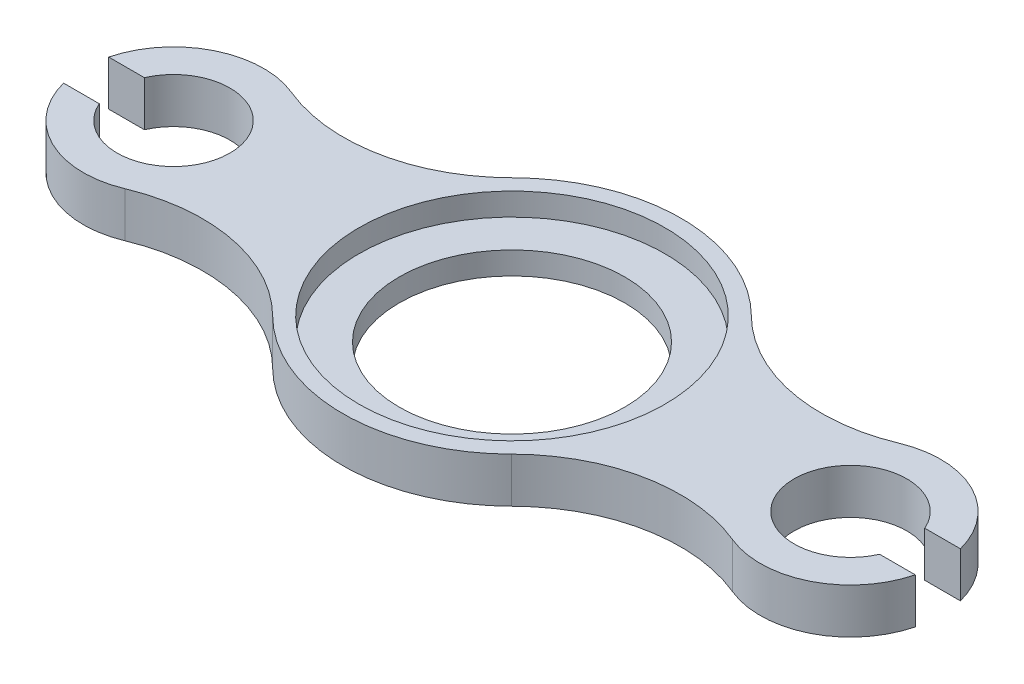
SolidWorks part; units mm, degrees
material "AISI 1020"
ref_plane "Plan de face" through (0, 0, 0) normal (0, 0, 1) x (1, 0, 0)
ref_plane "Plan de dessus" through (0, 0, 0) normal (0, 1, 0) x (1, 0, 0)
ref_plane "Plan de droite" through (0, 0, 0) normal (1, 0, 0) x (0, 0, -1)
sketch "Esquisse1" plane through (0, 0, 0) normal (0, 1, 0) x (1, 0, 0)
  line L0 (-362.0178, 0) -> (302.6706, 0) construction
  line L1 (0, 245.9199) -> (0, -219.9555) construction
  line L2 (-150, 208.8279) -> (-150, -184.3472) construction
  line L3 (150, 245.9199) -> (150, -239.2433) construction
  arc A0 (-52.9583, -53.1076) -> (52.9583, -53.1076) centre (0, 0) ccw
  arc A1 (-134.6667, 36.9444) -> (-134.6667, -36.9444) centre (-150, 0) ccw
  arc A3 (-134.6667, 36.9444) -> (-52.9583, 53.1076) centre (-105.9167, 106.2152) ccw
  arc A4 (-134.6667, -36.9444) -> (-52.9583, -53.1076) centre (-105.9167, -106.2152) cw
  arc A6 (134.6667, 36.9444) -> (134.6667, -36.9444) centre (150, 0) cw
  arc A7 (134.6667, -36.9444) -> (52.9583, -53.1076) centre (105.9167, -106.2152) ccw
  arc A8 (134.6667, 36.9444) -> (52.9583, 53.1076) centre (105.9167, 106.2152) cw
  arc A9 (52.9583, 53.1076) -> (-52.9583, 53.1076) centre (0, 0) ccw
  dimension "D3" = 150
  dimension "D4" = 80
  dimension "D6" = 150
  dimension "D1" = 150
  dimension "D2" = 150
extrude "Boss.-Extru.1" add sketch "Esquisse1" along normal blind 20
sketch "Esquisse2" plane through (0, 20, 0) normal (0, 1, 0) x (1, 0, 0)
  circle A0 centre (0, 0) radius 50
  dimension "D1" = 100
extrude "Enlèv. mat.-Extru.1" cut sketch "Esquisse2" against normal through all
sketch "Esquisse3" plane through (0, 20, 0) normal (0, 1, 0) x (1, 0, 0)
  circle A0 centre (0, 0) radius 67.8
  dimension "D1" = 135.6
extrude "Enlèv. mat.-Extru.2" cut sketch "Esquisse3" against normal blind 10
sketch "Esquisse4" plane through (0, 20, 0) normal (0, 1, 0) x (1, 0, 0)
  line L0 (0, 136.3023) -> (0, -137.5359) construction
  line L1 (-259.0361, 0) -> (262.3255, 0) construction
  circle A0 centre (-150, 0) radius 25
  circle A1 centre (150, 0) radius 25
  dimension "D1" = 50
extrude "Enlèv. mat.-Extru.4" cut sketch "Esquisse4" against normal through all
sketch "Esquisse5" plane through (0, 20, 0) normal (0, 1, 0) x (1, 0, 0)
  line L0 (-210.1071, 0) -> (235.1884, 0) construction
  line L1 (0, 119.8556) -> (0, -115.3328) construction
  line L2 (-188.7298, -10) -> (-172.9129, -10)
  line L3 (-188.7298, 10) -> (-172.9129, 10)
  line L4 (188.7298, -10) -> (172.9129, -10)
  line L5 (188.7298, 10) -> (172.9129, 10)
  arc A0 (-188.7298, 10) -> (-188.7298, -10) centre (-150, 0) ccw
  arc A1 (-172.9129, 10) -> (-172.9129, -10) centre (-150, 0) ccw
  arc A2 (188.7298, 10) -> (188.7298, -10) centre (150, 0) cw
  arc A3 (172.9129, 10) -> (172.9129, -10) centre (150, 0) cw
  dimension "D1" = 80
  dimension "D2" = 50
  dimension "D3" = 10
extrude "Enlèv. mat.-Extru.6" cut sketch "Esquisse5" against normal through all
